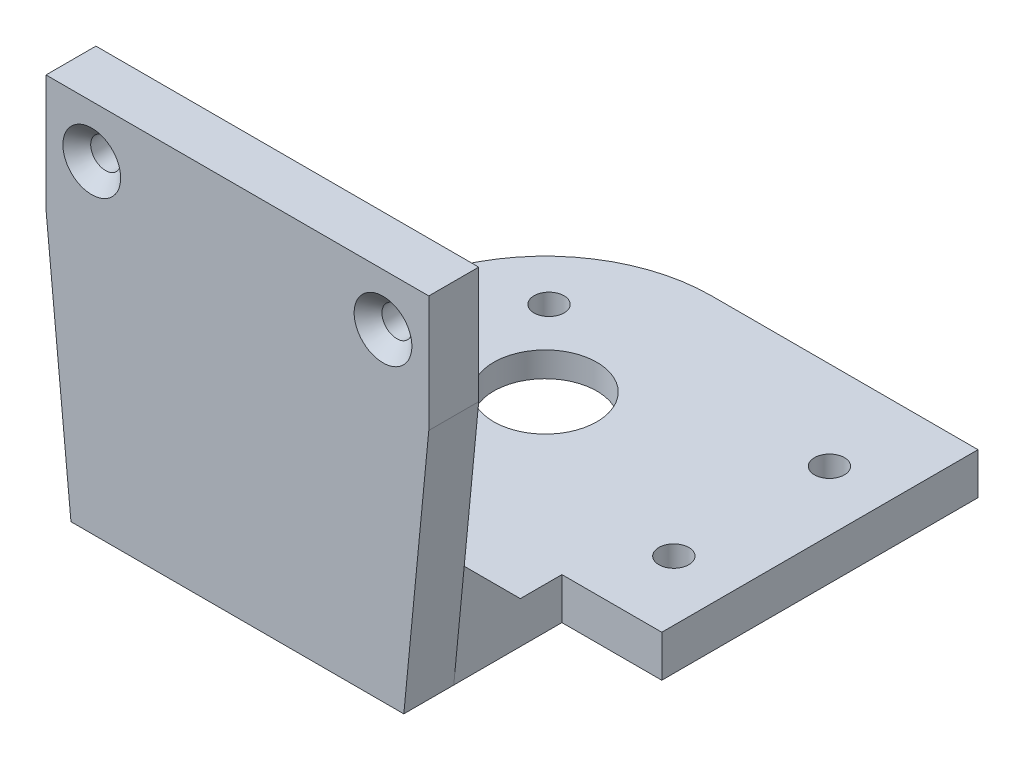
SolidWorks part; units mm, degrees
ref_plane "Płaszczyzna przednia" through (0, 0, 0) normal (0, 0, 1) x (1, 0, 0)
ref_plane "Płaszczyzna górna" through (0, 0, 0) normal (0, 1, 0) x (1, 0, 0)
ref_plane "Płaszczyzna prawa" through (0, 0, 0) normal (1, 0, 0) x (0, 0, -1)
sketch "Sketch1" plane through (0, 0, 0) normal (0, 1, 0) x (1, 0, 0)
  circle A0 centre (0, 0) radius 18
  circle A1 centre (0, 0) radius 6.2
  dimension "D1" = 36
  dimension "D2" = 12.4
extrude "Boss-Extrude1" add sketch "Sketch1" along normal blind 3
hole_wizard "M2 Clearance Hole1" [suppressed] positions "Sketch2" profile "Sketch4" hole size "M2" standard "DIN"
sketch "Sketch2" plane through (0, 3, 0) normal (0, 1, 0) x (1, 0, 0)
  circle A0 centre (0, 0) radius 8.5 construction
  point P4 (0, 8.5)
  point P10 (7.3612, -4.25)
  point P11 (-7.3612, -4.25)
  dimension "D1" = 17
  dimension "D2" = 3
sketch "Sketch4" plane through (-7.3612, 3, 4.25) normal (1, 0, 0) x (0, 0, 1)
  line L0 (0, 0) -> (0, 3)
  line L1 (0, 3) -> (1.1, 3)
  line L2 (1.1, 3) -> (1.1, 0)
  line L5 (1.1, 0) -> (0, 0)
  line L11 (0, -6.35) -> (0, 107.95) construction
  dimension "Thru Hole Dia." = 2.2
  dimension "Thru Hole Depth" = 3
sketch "Sketch5" plane through (0, 3, 0) normal (0, 1, 0) x (1, 0, 0)
  circle A0 centre (0, 0) radius 18 construction
  circle A1 centre (0, 0) radius 18
  circle A2 centre (0, 0) radius 20
  dimension "D1" = 2
extrude "Boss-Extrude2" add sketch "Sketch5" against normal blind 5
sketch "Sketch6" plane through (0, 3, 0) normal (0, 1, 0) x (1, 0, 0)
  line L0 (-20, 0) -> (-20, -31)
  line L1 (-20, -31) -> (20, -31)
  line L2 (20, -31) -> (20, 0)
  circle A0 centre (0, 0) radius 20 construction
  arc A1 (-20, 0) -> (20, 0) centre (0, 0) ccw
  dimension "D1" = 31
extrude "Boss-Extrude3" add sketch "Sketch6" against normal up to surface (5 mm away) up to face at (0, -2, 18)
sketch "Sketch7" plane through (0, 0, 31) normal (0, 0, 1) x (1, 0, 0)
  line L7 (20, -2) -> (20, 3) construction
  line L8 (-20, -2) -> (20, -2)
  line L9 (-20, -2) -> (-20, 43)
  line L10 (-20, 43) -> (20, 43)
  line L11 (20, -2) -> (20, 43)
  dimension "D1" = 45
extrude "Boss-Extrude4" add sketch "Sketch7" along normal blind 6
sketch "Sketch8" plane through (0, 0, 37) normal (0, 0, 1) x (1, 0, 0)
  line L1 (-23, 43) -> (23, 43)
  line L2 (-23, 43) -> (-23, 29)
  line L3 (-23, 29) -> (23, 29)
  line L4 (23, 43) -> (23, 29)
  line L6 (20, 43) -> (-20, 43) construction
  line L7 (23, 31.3811) -> (20, 31.3811) construction
  line L8 (20, -2) -> (20, 43) construction
  line L10 (-20, 43) -> (-20, -2) construction
  line L11 (-20, 40.157) -> (-23, 40.157) construction
  dimension "D1" = 46
  dimension "D3" = 14
extrude "Boss-Extrude5" add sketch "Sketch8" against normal up to surface (6 mm away) up to face at (0, 23, 31)
sketch "Sketch9" plane through (0, 0, 37) normal (0, 0, 1) x (1, 0, 0)
  line L0 (-23, 29) -> (-20, -2)
  line L1 (20, -2) -> (23, 29)
  line L2 (-20, 29) -> (-20, -2) construction
  line L3 (-23, 29) -> (-20, 29) construction
  line L4 (20, -2) -> (20, 29) construction
  line L5 (20, 29) -> (23, 29) construction
  line L6 (-20, 29) -> (-20, -2)
  line L7 (-23, 29) -> (-20, 29)
  line L8 (20, -2) -> (20, 29)
  line L9 (20, 29) -> (23, 29)
extrude "Boss-Extrude6" add sketch "Sketch9" against normal up to surface (6 mm away) up to face at (0, 26, 31)
chamfer "Chamfer1" distance 8 angle 45 1 edges at (0, 3, 31)
chamfer "Chamfer2" [suppressed] distance 3 angle 45
hole_wizard "CSK for M3 Hex Socket Countersunk Head Screw1" positions "Sketch10" profile "Sketch11" countersink size "M3" standard "DIN" end condition through all
sketch "Sketch10" plane through (0, 0, 37) normal (0, 0, 1) x (1, 0, 0)
  circle A0 centre (17.5, 36.7528) radius 2.1 construction
  circle A1 centre (-17.5, 36.7528) radius 2.1 construction
  point P0 (17.5, 36.7528)
  point P2 (-17.5, 36.7528)
sketch "Sketch11" plane through (17.5, 36.7528, 37) normal (1, 0, 0) x (0, -1, 0)
  line L0 (0, 0) -> (0, 57)
  line L1 (0, 57) -> (1.8, 57)
  line L2 (1.8, 57) -> (1.8, 1.67)
  line L3 (1.8, 1.67) -> (3.47, 0)
  line L5 (3.47, 0) -> (0, 0)
  line L6 (-1.8, 1.67) -> (-3.47, 0) construction
  line L11 (0, -6.35) -> (0, 107.95) construction
  dimension "Thru Hole Dia." = 3.6
  dimension "Thru Hole Depth" = 57
  dimension "Near C'Sink Dia." = 6.94
  dimension "Near C'Sink Angle" = 90
hole_wizard "M3 Clearance Hole2" [suppressed] positions "Sketch19" profile "Sketch20" hole size "M3" standard "DIN"
sketch "Sketch19" plane through (0, -2, 0) normal (0, -1, 0) x (-1, 0, 0)
  line L0 (9.35, 8.9) -> (0, 8.9)
  line L1 (0, 8.9) -> (-9.35, 8.9)
  line L3 (0, 8.9) -> (0, 0)
  point P0 (-9.35, 8.9)
  point P6 (9.35, 8.9)
  point P7 (9.35, -24.8)
  point P8 (-9.35, -24.8)
  dimension "D3" = 18.7
  dimension "D4" = 33.7
  dimension "D5" = 8.9
  dimension "D1" = 2
  dimension "D2" = 2
sketch "Sketch20" plane through (9.35, -2, -8.9) normal (1, 0, 0) x (0, 0, -1)
  line L0 (0, 0) -> (0, 45)
  line L1 (0, 45) -> (1.8, 45)
  line L2 (1.8, 45) -> (1.8, 0)
  line L5 (1.8, 0) -> (0, 0)
  line L11 (0, -6.35) -> (0, 107.95) construction
  dimension "Thru Hole Dia." = 3.6
  dimension "Thru Hole Depth" = 45
sketch "Sketch21" [suppressed] plane through (0, 3, 0) normal (0, 1, 0) x (1, 0, 0)
  circle A0 centre (-9.35, -24.8) radius 3.25
  circle A1 centre (9.35, -24.8) radius 3.25
  dimension "D1" = 6.5
extrude "Cut-Extrude1" [suppressed] cut sketch "Sketch21" along normal through all
sketch "Sketch22" [suppressed] plane through (0, -2, 0) normal (0, -1, 0) x (1, 0, 0)
  circle A0 centre (-9.35, 24.8) radius 4.25
  circle A1 centre (9.35, 24.8) radius 4.25
  dimension "D1" = 8.5
extrude "Cut-Extrude2" [suppressed] cut sketch "Sketch22" against normal up to surface and the other way through all
sketch "Sketch23" plane through (0, -2, 0) normal (0, -1, 0) x (1, 0, 0)
  line L0 (0, -20) -> (32, -20)
  line L1 (32, -20) -> (32, 18)
  line L2 (32, 18) -> (20, 18)
  line L3 (20, 0) -> (20, 31) construction
  line L4 (20, 0) -> (20, 18)
  arc A0 (-20, 0) -> (20, 0) centre (0, 0) ccw construction
  circle A1 centre (0, 0) radius 18 construction
  arc A2 (0, -20) -> (20, 0) centre (0, 0) ccw
  dimension "D1" = 12
extrude "Boss-Extrude7" add sketch "Sketch23" against normal up to surface (5 mm away) up to face at (0, 3, 6.2)
hole_wizard "M3 Clearance Hole3" positions "Sketch24" profile "Sketch25" hole size "M3" standard "DIN" end condition through all
sketch "Sketch24" plane through (0, -2, 0) normal (0, -1, 0) x (-1, 0, 0)
  line L0 (8.9, 9.35) -> (8.9, 0)
  line L1 (8.9, 0) -> (8.9, -9.35)
  line L3 (8.9, 0) -> (0, 0)
  point P0 (-24.8, 9.35)
  point P5 (8.9, 9.35)
  point P6 (8.9, -9.35)
  point P7 (-24.8, -9.35)
  dimension "D3" = 18.7
  dimension "D4" = 33.7
  dimension "D5" = 8.9
  dimension "D1" = 2
  dimension "D2" = 2
sketch "Sketch25" plane through (24.8, -2, -9.35) normal (1, 0, 0) x (0, 0, -1)
  line L0 (0, 0) -> (0, 45)
  line L1 (0, 45) -> (1.8, 45)
  line L2 (1.8, 45) -> (1.8, 0)
  line L5 (1.8, 0) -> (0, 0)
  line L11 (0, -6.35) -> (0, 107.95) construction
  dimension "Thru Hole Dia." = 3.6
  dimension "Thru Hole Depth" = 45
sketch "Sketch26" plane through (0, -2, 0) normal (0, -1, 0) x (1, 0, 0)
  circle A0 centre (24.8, 9.35) radius 4.25
  circle A1 centre (24.8, -9.35) radius 4.25
  dimension "D1" = 8.5
extrude "Cut-Extrude3" cut sketch "Sketch26" against normal up to surface (2 mm away) up to face at (-8.9, 0, -7.55)
